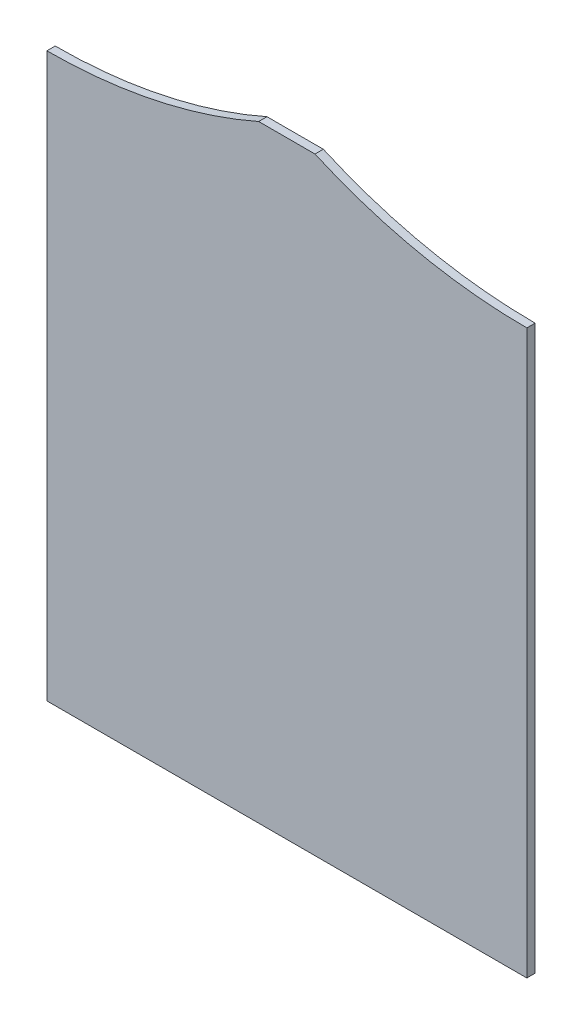
SolidWorks part; units mm, degrees
ref_plane "Front Plane" through (0, 0, 0) normal (0, 0, 1) x (1, 0, 0)
ref_plane "Top Plane" through (0, 0, 0) normal (0, 1, 0) x (1, 0, 0)
ref_plane "Right Plane" through (0, 0, 0) normal (1, 0, 0) x (0, 0, -1)
sketch "Sketch1" plane through (0, 0, 0) normal (0, 0, 1) x (1, 0, 0)
  line L0 (-59.8974, 103.1716) -> (-39.8974, 103.1716)
  line L2 (-135.1474, 87.3016) -> (-135.1474, -112.6984)
  line L3 (-135.1474, -112.6984) -> (35.3526, -112.6984)
  line L4 (35.3526, 87.3016) -> (35.3526, -112.6984)
  arc A0 (-135.1474, 87.3016) -> (-59.8974, 103.1716) centre (-135.1474, 273.6412) ccw
  arc A1 (-39.8974, 103.1716) -> (35.3526, 87.3016) centre (35.3526, 273.6412) ccw
  dimension "D1" = 200
  dimension "D2" = 170.5
  dimension "D4" = 20
  dimension "D3" = 15.87
extrude "Boss-Extrude1" add sketch "Sketch1" along normal blind 2.95
equation "\"Width\"= 170.5"
equation "\"Height\"= 200"
equation "\"thin Acrylic\"= 2.95"
equation "\"D1@Sketch1\"=\"Height\""
equation "\"D2@Sketch1\"=\"Width\""
equation "\"D1@Boss-Extrude1\"=\"thin Acrylic\""
equation "\"Thick acrylic\"= 5.63"
equation "\"Drone height\"= 21.5"
equation "\"Guard height\"= \"Drone height\" - \"Thick acrylic\""
equation "\"Support width\"= 20"
equation "\"D4@Sketch1\"=\"Support width\""
equation "\"D3@Sketch1\"=\"Guard height\""
